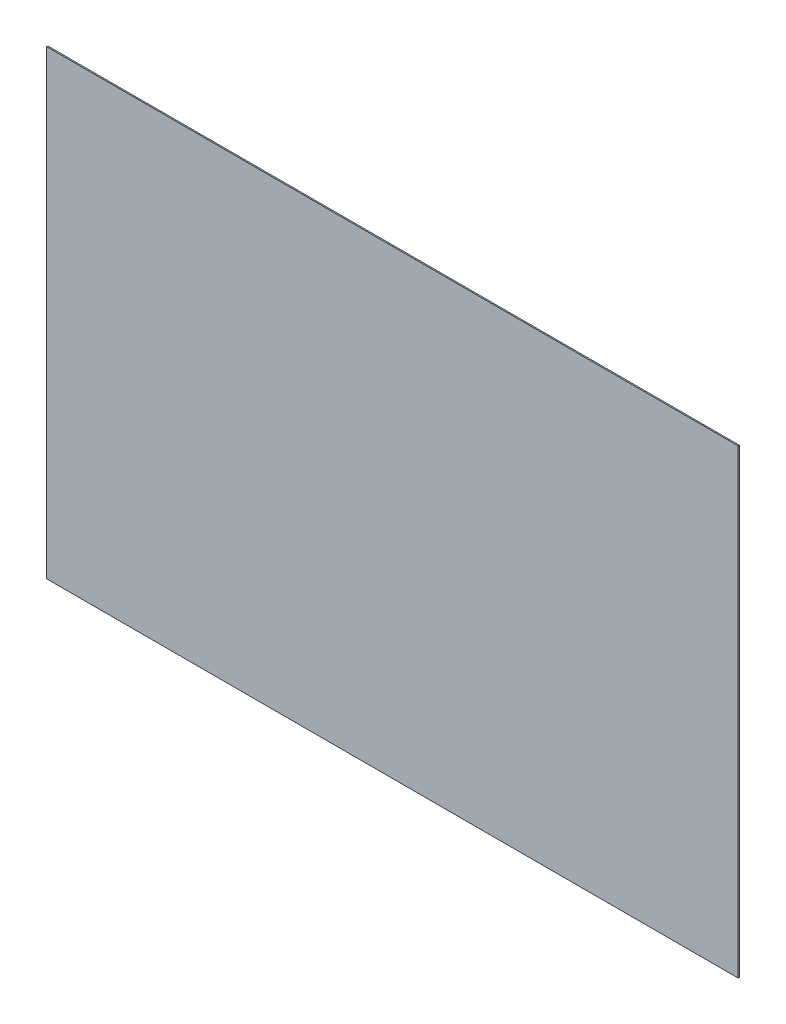
SolidWorks part; units mm, degrees
ref_plane "Front Plane" through (0, 0, 0) normal (0, 0, 1) x (1, 0, 0)
ref_plane "Top Plane" through (0, 0, 0) normal (0, 1, 0) x (1, 0, 0)
ref_plane "Right Plane" through (0, 0, 0) normal (1, 0, 0) x (0, 0, -1)
sketch "Sketch1" plane through (0, 0, 0) normal (0, 0, 1) x (1, 0, 0)
  line L1 (-457.2, -304.8) -> (457.2, -304.8)
  line L2 (-457.2, -304.8) -> (-457.2, 304.8)
  line L3 (-457.2, 304.8) -> (457.2, 304.8)
  line L4 (457.2, -304.8) -> (457.2, 304.8)
  line L5 (0, 304.8) -> (0, -304.8) construction
  line L6 (-457.2, 0) -> (457.2, 0) construction
  point P0 (0, 0)
  point P4 (-320.04, 0)
  point P5 (320.04, 0)
  point P6 (0, 213.36)
  point P7 (0, -213.36)
  dimension "Length" = 914.4
  dimension "Width" = 609.6
  dimension "Break" = 137.16
  dimension "D2" = 137.16
  dimension "D1" = 91.44
  dimension "D3" = 91.44
sketch "Sketch2" plane through (0, 0, 0) normal (1, 0, 0) x (0, 0, -1)
  line L0 (-0.7938, -304.8) -> (0.7938, -304.8)
  dimension "Thickness" = 1.5875
sketch "Sketch3" plane through (0, 0, 0) normal (0, 0, 1) x (1, 0, 0)
  line L0 (-457.2, -304.8) -> (-457.2, 304.8) construction
  line L1 (-457.2, -304.8) -> (457.2, -304.8) construction
  line L2 (457.2, -304.8) -> (457.2, 304.8) construction
  line L3 (-457.2, 304.8) -> (457.2, 304.8) construction
  line L4 (-457.2, -304.8) -> (-457.2, 304.8)
  line L5 (-457.2, -304.8) -> (457.2, -304.8)
  line L6 (457.2, -304.8) -> (457.2, 304.8)
  line L7 (-457.2, 304.8) -> (457.2, 304.8)
extrude "Boss-Extrude1" add sketch "Sketch3" along normal mid plane 1.5875
equation "\"D1@Boss-Extrude1\"=\"thickness@sketch2\""
equation "\"Break@Sketch1\" = \"Length@Sketch1\" * 0.15"
equation "\"D2@Sketch1\" = \"Break@Sketch1\""
equation "\"D1@Sketch1\"=\"Width@Sketch1\"*0.15"
equation "\"D3@Sketch1\"=\"D1@Sketch1\""
